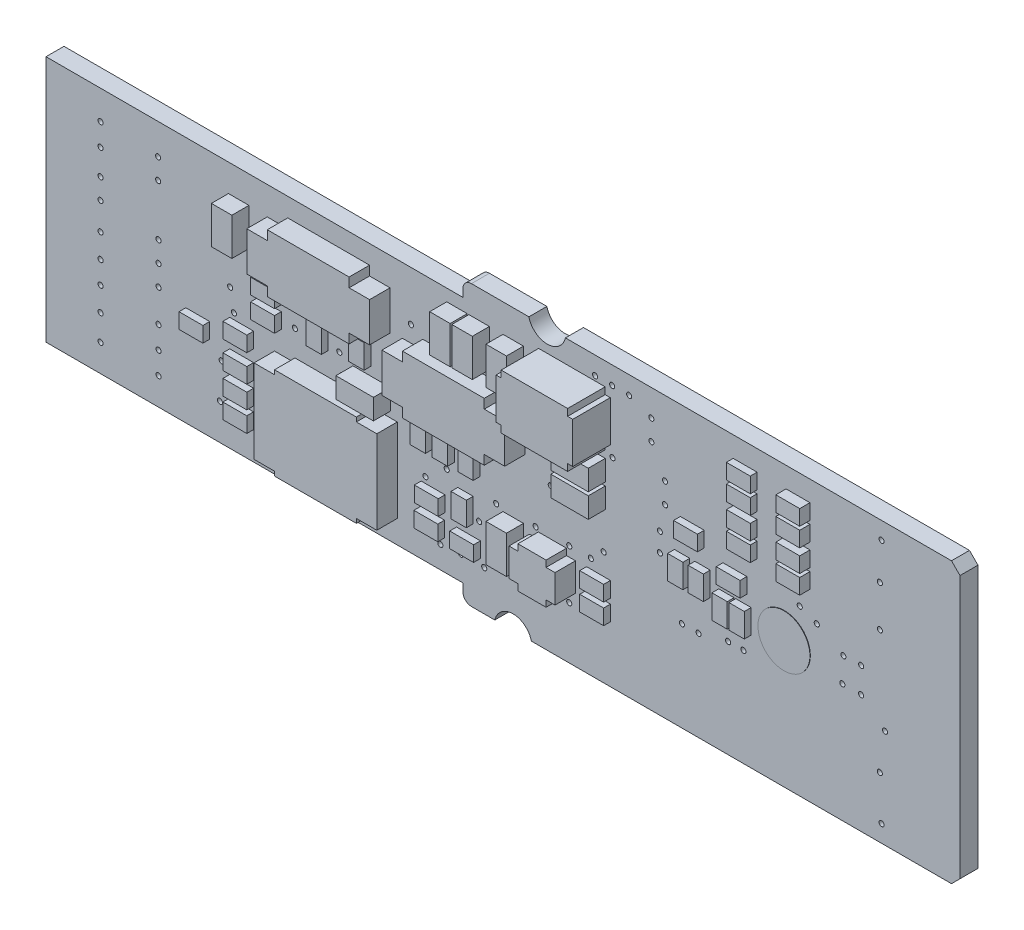
SolidWorks part; units mm, degrees
ref_plane "Front Plane" through (0, 0, 0) normal (0, 0, 1) x (1, 0, 0)
ref_plane "Top Plane" through (0, 0, 0) normal (0, 1, 0) x (1, 0, 0)
ref_plane "Right Plane" through (0, 0, 0) normal (1, 0, 0) x (0, 0, -1)
sketch "Sketch1" plane through (0, 0, 0) normal (0, 0, 1) x (1, 0, 0)
  line L0 (24.45, 14.95) -> (24.45, 14.5)
  line L1 (24.45, 14.5) -> (2.3285, 14.5)
  line L2 (2.3285, 14.5) -> (0.2516, 14.5)
  line L3 (0.2516, 14.5) -> (0, 14.5)
  line L4 (0, 14.5) -> (0, 13.75)
  line L5 (0, 13.75) -> (0, 0.75)
  line L6 (0, 0.75) -> (0, 0)
  line L7 (0, 0) -> (0.2516, 0)
  line L8 (0.2516, 0) -> (2.3285, 0)
  line L9 (2.3285, 0) -> (24.45, 0)
  line L10 (24.45, 0) -> (24.45, -0.45)
  line L11 (24.95, -0.95) -> (26.1285, -0.95)
  line L12 (26.1285, -0.95) -> (26.3188, -0.95)
  line L13 (28.4613, -0.95) -> (45.34, -0.95)
  line L14 (45.34, -0.95) -> (47.34, -0.95)
  line L15 (47.34, -0.95) -> (53.1, -0.95)
  line L16 (53.1, -0.95) -> (53.6, -0.45)
  line L17 (53.6, -0.45) -> (53.6, 14.95)
  line L18 (53.6, 14.95) -> (53.1, 15.45)
  line L19 (53.1, 15.45) -> (47.34, 15.45)
  line L20 (47.34, 15.45) -> (45.34, 15.45)
  line L21 (45.34, 15.45) -> (30.4613, 15.45)
  line L22 (28.3188, 15.45) -> (27.1285, 15.45)
  line L23 (27.1285, 15.45) -> (25.2516, 15.45)
  line L24 (25.2516, 15.45) -> (24.95, 15.45)
  arc A0 (24.95, 15.45) -> (24.45, 14.95) centre (24.95, 14.95) ccw
  arc A1 (24.45, -0.45) -> (24.95, -0.95) centre (24.95, -0.45) ccw
  arc A2 (26.3188, -0.95) -> (28.4613, -0.95) centre (27.39, -1.1999) cw
  arc A3 (30.4613, 15.45) -> (28.3188, 15.45) centre (29.3901, 15.7) cw
extrude "BOARD" add sketch "Sketch1" along normal blind 1.055 separate body
sketch "Sketch2" plane through (0, 0, 0) normal (0, 0, 1) x (1, 0, 0)
  circle A0 centre (31.95, 5) radius 0.15
  circle A1 centre (38.2697, 4.3492) radius 0.15
  circle A2 centre (37.2889, 4.3492) radius 0.15
  circle A3 centre (21, 7.3) radius 0.15
  circle A4 centre (26.4, 3.6) radius 0.15
  circle A5 centre (10.3, 4.2) radius 0.15
  circle A6 centre (11.025, 7) radius 0.15
  circle A7 centre (12.1, 10.1) radius 0.15
  circle A8 centre (22.9, 7.6) radius 0.15
  circle A9 centre (16.1, 9.8) radius 0.15
  circle A10 centre (29.6, 10.1) radius 0.15
  circle A11 centre (29, 10.8) radius 0.15
  circle A12 centre (25.4, 3.6) radius 0.15
  circle A13 centre (10.8, 8.2) radius 0.15
  circle A14 centre (47.8, 7.4841) radius 0.15
  circle A15 centre (46.76, 7.46) radius 0.15
  circle A16 centre (30.5, 7.5) radius 0.15
  circle A17 centre (29.6, 7.5) radius 0.15
  circle A18 centre (6.575, 11.5) radius 0.15
  circle A19 centre (6.575, 12.7) radius 0.15
  circle A20 centre (10.2, 2.1) radius 0.15
  circle A21 centre (6.6, 4.2) radius 0.15
  circle A22 centre (6.6, 2.9) radius 0.15
  circle A23 centre (6.6, 1.6) radius 0.15
  circle A24 centre (47.8, 6) radius 0.15
  circle A25 centre (23, 11.927) radius 0.15
  circle A26 centre (23, 11.1) radius 0.15
  circle A27 centre (46.7, 6) radius 0.15
  circle A28 centre (23.125, 1.3) radius 0.15
  circle A29 centre (14.6, 9.25) radius 0.15
  circle A30 centre (14.6, 8) radius 0.15
  circle A31 centre (28.715, 4.985) radius 0.15
  circle A32 centre (17.2, 8.1) radius 0.15
  circle A33 centre (32.7, 5.7) radius 0.15
  circle A34 centre (30.685, 2.115) radius 0.15
  circle A35 centre (35.5, 13.9) radius 0.15
  circle A36 centre (35.5, 12.7) radius 0.15
  circle A37 centre (36.3, 11.1) radius 0.15
  circle A38 centre (36.3, 9.9) radius 0.15
  circle A39 centre (36, 7.3) radius 0.15
  circle A40 centre (24.325, 1.4) radius 0.15
  circle A41 centre (22.25, 4.3) radius 0.15
  circle A42 centre (36, 8.4) radius 0.15
  circle A43 centre (23.5, 5.3) radius 0.15
  circle A44 centre (44.2, 8.7) radius 0.15
  circle A45 centre (40.9, 4.8) radius 0.15
  circle A46 centre (40, 4.8) radius 0.15
  circle A47 centre (45.2, 8.3) radius 0.15
  circle A48 centre (6.6, 8.5) radius 0.15
  circle A49 centre (6.6, 7.3) radius 0.15
  circle A50 centre (6.6, 6.1) radius 0.15
  circle A51 centre (25.8, 7.1) radius 0.15
  circle A52 centre (17.4, 7) radius 0.15
  circle A53 centre (26.4, 5) radius 0.15
  circle A54 centre (30.685, 5) radius 0.15
  circle A55 centre (25.7, 1.4) radius 0.15
  circle A56 centre (12.4, 1.2) radius 0.15
  circle A57 centre (3.2, 12.8) radius 0.15
  circle A58 centre (49, 0.05) radius 0.15
  circle A59 centre (48.9, 2.6) radius 0.15
  circle A60 centre (48.9, 9.85) radius 0.15
  circle A61 centre (49.2, 4.85) radius 0.15
  circle A62 centre (48.9, 12.25) radius 0.15
  circle A63 centre (33.22, 10.75) radius 0.15
  circle A64 centre (32.2, 14.4) radius 0.15
  circle A65 centre (33.2, 14.4) radius 0.15
  circle A66 centre (34.2, 14.4) radius 0.15
  circle A67 centre (49, 14.4443) radius 0.15
  circle A68 centre (3.2, 11.5) radius 0.15
  circle A69 centre (3.2, 10) radius 0.15
  circle A70 centre (3.2, 8.8) radius 0.15
  circle A71 centre (3.2, 7.2) radius 0.15
  circle A72 centre (3.2, 5.8) radius 0.15
  circle A73 centre (3.2, 4.5) radius 0.15
  circle A74 centre (3.2, 3.1) radius 0.15
  circle A75 centre (3.2, 1.6) radius 0.15
  circle A76 centre (21.4, 11.6) radius 0.15
extrude "PLATED HOLES" cut sketch "Sketch2" along normal through all
ref_plane "Plane1" through (0, 0, 1.055) normal (0, 0, 1) x (1, 0, 0)
sketch "Sketch3" plane through (0, 0, 1.055) normal (0, 0, 1) x (1, 0, 0)
  line L0 (40.3, 10.75) -> (40.3, 9.85)
  line L1 (40.3, 9.85) -> (41.7, 9.85)
  line L2 (41.7, 9.85) -> (41.7, 10.75)
  line L3 (41.7, 10.75) -> (40.3, 10.75)
extrude "R0201NAS-1" add sketch "Sketch3" along normal blind 0.4 separate body
sketch "Sketch4" plane through (0, 0, 1.055) normal (0, 0, 1) x (1, 0, 0)
  line L0 (25.475, 1.75) -> (25.475, 2.65)
  line L1 (25.475, 2.65) -> (24.075, 2.65)
  line L2 (24.075, 2.65) -> (24.075, 1.75)
  line L3 (24.075, 1.75) -> (25.475, 1.75)
extrude "R0201NAS-2" add sketch "Sketch4" along normal blind 0.4 separate body
sketch "Sketch5" plane through (0, 0, 1.055) normal (0, 0, 1) x (1, 0, 0)
  line L0 (23.375, 1.75) -> (23.375, 2.65)
  line L1 (23.375, 2.65) -> (21.975, 2.65)
  line L2 (21.975, 2.65) -> (21.975, 1.75)
  line L3 (21.975, 1.75) -> (23.375, 1.75)
extrude "R0201NAS-3" add sketch "Sketch5" along normal blind 0.4 separate body
sketch "Sketch6" plane through (0, 0, 1.055) normal (0, 0, 1) x (1, 0, 0)
  line L0 (8.2, 5.85) -> (8.2, 4.95)
  line L1 (8.2, 4.95) -> (9.6, 4.95)
  line L2 (9.6, 4.95) -> (9.6, 5.85)
  line L3 (9.6, 5.85) -> (8.2, 5.85)
extrude "R0201NAS-4" add sketch "Sketch6" along normal blind 0.4 separate body
sketch "Sketch7" plane through (0, 0, 1.055) normal (0, 0, 1) x (1, 0, 0)
  line L0 (10.775, 2.55) -> (10.775, 1.65)
  line L1 (10.775, 1.65) -> (12.175, 1.65)
  line L2 (12.175, 1.65) -> (12.175, 2.55)
  line L3 (12.175, 2.55) -> (10.775, 2.55)
extrude "R0201NAS-5" add sketch "Sketch7" along normal blind 0.4 separate body
sketch "Sketch8" plane through (0, 0, 1.055) normal (0, 0, 1) x (1, 0, 0)
  line L0 (10.775, 3.75) -> (10.775, 2.85)
  line L1 (10.775, 2.85) -> (12.175, 2.85)
  line L2 (12.175, 2.85) -> (12.175, 3.75)
  line L3 (12.175, 3.75) -> (10.775, 3.75)
extrude "R0201NAS-6" add sketch "Sketch8" along normal blind 0.4 separate body
sketch "Sketch9" plane through (0, 0, 1.055) normal (0, 0, 1) x (1, 0, 0)
  line L0 (24.55, 5.9) -> (25.45, 5.9)
  line L1 (25.45, 5.9) -> (25.45, 7.3)
  line L2 (25.45, 7.3) -> (24.55, 7.3)
  line L3 (24.55, 7.3) -> (24.55, 5.9)
extrude "R0201NAS-7" add sketch "Sketch9" along normal blind 0.4 separate body
sketch "Sketch10" plane through (0, 0, 1.055) normal (0, 0, 1) x (1, 0, 0)
  line L0 (21.75, 5.875) -> (22.65, 5.875)
  line L1 (22.65, 5.875) -> (22.65, 7.275)
  line L2 (22.65, 7.275) -> (21.75, 7.275)
  line L3 (21.75, 7.275) -> (21.75, 5.875)
extrude "R0201NAS-8" add sketch "Sketch10" along normal blind 0.4 separate body
sketch "Sketch11" plane through (0, 0, 1.055) normal (0, 0, 1) x (1, 0, 0)
  line L0 (12.175, 5.75) -> (12.175, 6.65)
  line L1 (12.175, 6.65) -> (10.775, 6.65)
  line L2 (10.775, 6.65) -> (10.775, 5.75)
  line L3 (10.775, 5.75) -> (12.175, 5.75)
extrude "R0201NAS-9" add sketch "Sketch11" along normal blind 0.4 separate body
sketch "Sketch12" plane through (0, 0, 1.055) normal (0, 0, 1) x (1, 0, 0)
  line L0 (12.175, 4.15) -> (12.175, 5.05)
  line L1 (12.175, 5.05) -> (10.775, 5.05)
  line L2 (10.775, 5.05) -> (10.775, 4.15)
  line L3 (10.775, 4.15) -> (12.175, 4.15)
extrude "R0201NAS-10" add sketch "Sketch12" along normal blind 0.4 separate body
sketch "Sketch13" plane through (0, 0, 1.055) normal (0, 0, 1) x (1, 0, 0)
  line L0 (13.8, 8.8) -> (13.8, 9.7)
  line L1 (13.8, 9.7) -> (12.4, 9.7)
  line L2 (12.4, 9.7) -> (12.4, 8.8)
  line L3 (12.4, 8.8) -> (13.8, 8.8)
extrude "R0201NAS-11" add sketch "Sketch13" along normal blind 0.4 separate body
sketch "Sketch14" plane through (0, 0, 1.055) normal (0, 0, 1) x (1, 0, 0)
  line L0 (19.05, 9.7) -> (18.15, 9.7)
  line L1 (18.15, 9.7) -> (18.15, 8.3)
  line L2 (18.15, 8.3) -> (19.05, 8.3)
  line L3 (19.05, 8.3) -> (19.05, 9.7)
extrude "R0201NAS-12" add sketch "Sketch14" along normal blind 0.4 separate body
sketch "Sketch15" plane through (0, 0, 1.055) normal (0, 0, 1) x (1, 0, 0)
  line L0 (22, 3.95) -> (22, 3.05)
  line L1 (22, 3.05) -> (23.4, 3.05)
  line L2 (23.4, 3.05) -> (23.4, 3.95)
  line L3 (23.4, 3.95) -> (22, 3.95)
extrude "R0201NAS-13" add sketch "Sketch15" along normal blind 0.4 separate body
sketch "Sketch16" plane through (0, 0, 1.055) normal (0, 0, 1) x (1, 0, 0)
  line L0 (25.05, 4.7) -> (24.15, 4.7)
  line L1 (24.15, 4.7) -> (24.15, 3.3)
  line L2 (24.15, 3.3) -> (25.05, 3.3)
  line L3 (25.05, 3.3) -> (25.05, 4.7)
extrude "R0201NAS-14" add sketch "Sketch16" along normal blind 0.4 separate body
sketch "Sketch17" plane through (0, 0, 1.055) normal (0, 0, 1) x (1, 0, 0)
  line L0 (23.05, 5.875) -> (23.95, 5.875)
  line L1 (23.95, 5.875) -> (23.95, 7.275)
  line L2 (23.95, 7.275) -> (23.05, 7.275)
  line L3 (23.05, 7.275) -> (23.05, 5.875)
extrude "R0201NAS-15" add sketch "Sketch17" along normal blind 0.4 separate body
sketch "Sketch18" plane through (0, 0, 1.055) normal (0, 0, 1) x (1, 0, 0)
  line L0 (13.8, 7.55) -> (13.8, 8.45)
  line L1 (13.8, 8.45) -> (12.4, 8.45)
  line L2 (12.4, 8.45) -> (12.4, 7.55)
  line L3 (12.4, 7.55) -> (13.8, 7.55)
extrude "R0201NAS-16" add sketch "Sketch18" along normal blind 0.4 separate body
sketch "Sketch19" plane through (0, 0, 1.055) normal (0, 0, 1) x (1, 0, 0)
  line L0 (15.65, 7.85) -> (16.55, 7.85)
  line L1 (16.55, 7.85) -> (16.55, 9.25)
  line L2 (16.55, 9.25) -> (15.65, 9.25)
  line L3 (15.65, 9.25) -> (15.65, 7.85)
extrude "R0201NAS-17" add sketch "Sketch19" along normal blind 0.4 separate body
sketch "Sketch20" plane through (0, 0, 1.055) normal (0, 0, 1) x (1, 0, 0)
  line L0 (31.7, 3.25) -> (31.7, 2.35)
  line L1 (31.7, 2.35) -> (33.1, 2.35)
  line L2 (33.1, 2.35) -> (33.1, 3.25)
  line L3 (33.1, 3.25) -> (31.7, 3.25)
extrude "R0201NAS-18" add sketch "Sketch20" along normal blind 0.4 separate body
sketch "Sketch21" plane through (0, 0, 1.055) normal (0, 0, 1) x (1, 0, 0)
  line L0 (31.7, 4.45) -> (31.7, 3.55)
  line L1 (31.7, 3.55) -> (33.1, 3.55)
  line L2 (33.1, 3.55) -> (33.1, 4.45)
  line L3 (33.1, 4.45) -> (31.7, 4.45)
extrude "R0201NAS-19" add sketch "Sketch21" along normal blind 0.4 separate body
sketch "Sketch22" plane through (0, 0, 0) normal (0, 0, 1) x (1, 0, 0)
  line L0 (39.25, 11.2) -> (40.15, 11.2)
  line L1 (40.15, 11.2) -> (40.15, 9.8)
  line L2 (40.15, 9.8) -> (39.25, 9.8)
  line L3 (39.25, 9.8) -> (39.25, 11.2)
extrude "R0201NAS-20" add sketch "Sketch22" against normal blind 0.4 separate body
sketch "Sketch23" plane through (0, 0, 0) normal (0, 0, 1) x (1, 0, 0)
  line L0 (39.25, 14) -> (40.15, 14)
  line L1 (40.15, 14) -> (40.15, 12.6)
  line L2 (40.15, 12.6) -> (39.25, 12.6)
  line L3 (39.25, 12.6) -> (39.25, 14)
extrude "R0201NAS-21" add sketch "Sketch23" against normal blind 0.4 separate body
sketch "Sketch24" plane through (0, 0, 1.055) normal (0, 0, 1) x (1, 0, 0)
  line L0 (41.1, 7.75) -> (41.1, 8.65)
  line L1 (41.1, 8.65) -> (39.7, 8.65)
  line L2 (39.7, 8.65) -> (39.7, 7.75)
  line L3 (39.7, 7.75) -> (41.1, 7.75)
extrude "R0201NAS-22" add sketch "Sketch24" along normal blind 0.4 separate body
sketch "Sketch25" plane through (0, 0, 1.055) normal (0, 0, 1) x (1, 0, 0)
  line L0 (38.6, 8.85) -> (38.6, 9.75)
  line L1 (38.6, 9.75) -> (37.2, 9.75)
  line L2 (37.2, 9.75) -> (37.2, 8.85)
  line L3 (37.2, 8.85) -> (38.6, 8.85)
extrude "R0201NAS-23" add sketch "Sketch25" along normal blind 0.4 separate body
sketch "Sketch26" plane through (0, 0, 0) normal (0, 0, 1) x (1, 0, 0)
  line L0 (41, 13.35) -> (41, 14.25)
  line L1 (41, 14.25) -> (42.4, 14.25)
  line L2 (42.4, 14.25) -> (42.4, 13.35)
  line L3 (42.4, 13.35) -> (41, 13.35)
extrude "R0201NAS-24" add sketch "Sketch26" against normal blind 0.4 separate body
sketch "Sketch27" plane through (0, 0, 1.055) normal (0, 0, 1) x (1, 0, 0)
  line L0 (40.45, 5.8) -> (41.35, 5.8)
  line L1 (41.35, 5.8) -> (41.35, 7.2)
  line L2 (41.35, 7.2) -> (40.45, 7.2)
  line L3 (40.45, 7.2) -> (40.45, 5.8)
extrude "R0201NAS-25" add sketch "Sketch27" along normal blind 0.4 separate body
sketch "Sketch28" plane through (0, 0, 1.055) normal (0, 0, 1) x (1, 0, 0)
  line L0 (40.3, 11.85) -> (40.3, 10.95)
  line L1 (40.3, 10.95) -> (41.7, 10.95)
  line L2 (41.7, 10.95) -> (41.7, 11.85)
  line L3 (41.7, 11.85) -> (40.3, 11.85)
extrude "R0201NAS-26" add sketch "Sketch28" along normal blind 0.4 separate body
sketch "Sketch29" plane through (0, 0, 1.055) normal (0, 0, 1) x (1, 0, 0)
  line L0 (39.45, 5.8) -> (40.35, 5.8)
  line L1 (40.35, 5.8) -> (40.35, 7.2)
  line L2 (40.35, 7.2) -> (39.45, 7.2)
  line L3 (39.45, 7.2) -> (39.45, 5.8)
extrude "R0201NAS-27" add sketch "Sketch29" along normal blind 0.4 separate body
sketch "Sketch30" plane through (0, 0, 1.055) normal (0, 0, 1) x (1, 0, 0)
  line L0 (40.3, 13.15) -> (40.3, 12.25)
  line L1 (40.3, 12.25) -> (41.7, 12.25)
  line L2 (41.7, 12.25) -> (41.7, 13.15)
  line L3 (41.7, 13.15) -> (40.3, 13.15)
extrude "R0201NAS-28" add sketch "Sketch30" along normal blind 0.4 separate body
sketch "Sketch31" plane through (0, 0, 1.055) normal (0, 0, 1) x (1, 0, 0)
  line L0 (38.05, 6.5) -> (38.95, 6.5)
  line L1 (38.95, 6.5) -> (38.95, 7.9)
  line L2 (38.95, 7.9) -> (38.05, 7.9)
  line L3 (38.05, 7.9) -> (38.05, 6.5)
extrude "R0201NAS-29" add sketch "Sketch31" along normal blind 0.4 separate body
sketch "Sketch32" plane through (0, 0, 1.055) normal (0, 0, 1) x (1, 0, 0)
  line L0 (40.3, 14.25) -> (40.3, 13.35)
  line L1 (40.3, 13.35) -> (41.7, 13.35)
  line L2 (41.7, 13.35) -> (41.7, 14.25)
  line L3 (41.7, 14.25) -> (40.3, 14.25)
extrude "R0201NAS-30" add sketch "Sketch32" along normal blind 0.4 separate body
sketch "Sketch33" plane through (0, 0, 0) normal (0, 0, 1) x (1, 0, 0)
  line L0 (37.3, 9.55) -> (37.3, 10.45)
  line L1 (37.3, 10.45) -> (38.7, 10.45)
  line L2 (38.7, 10.45) -> (38.7, 9.55)
  line L3 (38.7, 9.55) -> (37.3, 9.55)
extrude "R0201NAS-31" add sketch "Sketch33" against normal blind 0.4 separate body
sketch "Sketch34" plane through (0, 0, 0) normal (0, 0, 1) x (1, 0, 0)
  line L0 (41, 9.45) -> (41, 10.35)
  line L1 (41, 10.35) -> (42.4, 10.35)
  line L2 (42.4, 10.35) -> (42.4, 9.45)
  line L3 (42.4, 9.45) -> (41, 9.45)
extrude "R0201NAS-32" add sketch "Sketch34" against normal blind 0.4 separate body
sketch "Sketch35" plane through (0, 0, 0) normal (0, 0, 1) x (1, 0, 0)
  line L0 (37.3, 10.55) -> (37.3, 11.45)
  line L1 (37.3, 11.45) -> (38.7, 11.45)
  line L2 (38.7, 11.45) -> (38.7, 10.55)
  line L3 (38.7, 10.55) -> (37.3, 10.55)
extrude "R0201NAS-33" add sketch "Sketch35" against normal blind 0.4 separate body
sketch "Sketch36" plane through (0, 0, 0) normal (0, 0, 1) x (1, 0, 0)
  line L0 (41, 10.55) -> (41, 11.45)
  line L1 (41, 11.45) -> (42.4, 11.45)
  line L2 (42.4, 11.45) -> (42.4, 10.55)
  line L3 (42.4, 10.55) -> (41, 10.55)
extrude "R0201NAS-34" add sketch "Sketch36" against normal blind 0.4 separate body
sketch "Sketch37" plane through (0, 0, 0) normal (0, 0, 1) x (1, 0, 0)
  line L0 (37.3, 12.25) -> (37.3, 13.15)
  line L1 (37.3, 13.15) -> (38.7, 13.15)
  line L2 (38.7, 13.15) -> (38.7, 12.25)
  line L3 (38.7, 12.25) -> (37.3, 12.25)
extrude "R0201NAS-35" add sketch "Sketch37" against normal blind 0.4 separate body
sketch "Sketch38" plane through (0, 0, 0) normal (0, 0, 1) x (1, 0, 0)
  line L0 (41, 12.25) -> (41, 13.15)
  line L1 (41, 13.15) -> (42.4, 13.15)
  line L2 (42.4, 13.15) -> (42.4, 12.25)
  line L3 (42.4, 12.25) -> (41, 12.25)
extrude "R0201NAS-36" add sketch "Sketch38" against normal blind 0.4 separate body
sketch "Sketch39" plane through (0, 0, 0) normal (0, 0, 1) x (1, 0, 0)
  line L0 (37.3, 13.35) -> (37.3, 14.25)
  line L1 (37.3, 14.25) -> (38.7, 14.25)
  line L2 (38.7, 14.25) -> (38.7, 13.35)
  line L3 (38.7, 13.35) -> (37.3, 13.35)
extrude "R0201NAS-37" add sketch "Sketch39" against normal blind 0.4 separate body
sketch "Sketch40" plane through (0, 0, 1.055) normal (0, 0, 1) x (1, 0, 0)
  line L0 (36.85, 6.5) -> (37.75, 6.5)
  line L1 (37.75, 6.5) -> (37.75, 7.9)
  line L2 (37.75, 7.9) -> (36.85, 7.9)
  line L3 (36.85, 7.9) -> (36.85, 6.5)
extrude "R0201NAS-38" add sketch "Sketch40" along normal blind 0.4 separate body
sketch "J0M09NAS_CE-1 [0]" plane through (0, 0, 1.055) normal (0, 0, 1) x (1, 0, 0)
  line L0 (50.35, -0.5) -> (50.35, 15)
  line L1 (50.35, 15) -> (53.3, 15)
  line L2 (53.3, 15) -> (53.3, -0.5)
  line L3 (53.3, -0.5) -> (50.35, -0.5)
sketch "Sketch42" plane through (0, 0, 0) normal (0, 0, 1) x (1, 0, 0)
  circle A0 centre (35, 3.8) radius 1.524
extrude "FIDGLOBAL-1" add sketch "Sketch42" against normal blind 0.0254 separate body
sketch "Sketch43" plane through (0, 0, 1.055) normal (0, 0, 1) x (1, 0, 0)
  circle A0 centre (43.3, 6.5) radius 1.524
extrude "FIDGLOBAL-2" add sketch "Sketch43" along normal blind 0.0254 separate body
sketch "Sketch44" plane through (0, 0, 0) normal (0, 0, 1) x (1, 0, 0)
  line L0 (0.475, 9.3) -> (0.475, 5.2)
  line L1 (0.475, 5.2) -> (9.325, 5.2)
  line L2 (9.325, 5.2) -> (9.325, 9.3)
  line L3 (9.325, 9.3) -> (0.475, 9.3)
extrude "R0203NAS_CE-1" add sketch "Sketch44" against normal blind 0.7 separate body
sketch "Sketch45" plane through (0, 0, 0) normal (0, 0, 1) x (1, 0, 0)
  line L0 (0.45, 13.5) -> (0.45, 9.4)
  line L1 (0.45, 9.4) -> (9.3, 9.4)
  line L2 (9.3, 9.4) -> (9.3, 13.5)
  line L3 (9.3, 13.5) -> (0.45, 13.5)
extrude "R0203NAS_CE-2" add sketch "Sketch45" against normal blind 0.7 separate body
sketch "Sketch46" plane through (0, 0, 0) normal (0, 0, 1) x (1, 0, 0)
  line L0 (0.45, 5.1) -> (0.45, 1)
  line L1 (0.45, 1) -> (9.3, 1)
  line L2 (9.3, 1) -> (9.3, 5.1)
  line L3 (9.3, 5.1) -> (0.45, 5.1)
extrude "R0203NAS_CE-3" add sketch "Sketch46" against normal blind 0.7 separate body
sketch "Sketch47" plane through (0, 0, 1.055) normal (0, 0, 1) x (1, 0, 0)
  line L0 (28.59, 13.73) -> (28.59, 11.33)
  line L1 (28.59, 11.33) -> (28.89, 11.33)
  line L2 (28.89, 11.33) -> (28.89, 10.93)
  line L3 (28.89, 10.93) -> (32.79, 10.93)
  line L4 (32.79, 10.93) -> (32.79, 11.33)
  line L5 (32.79, 11.33) -> (33.09, 11.33)
  line L6 (33.09, 11.33) -> (33.09, 13.73)
  line L7 (33.09, 13.73) -> (32.79, 13.73)
  line L8 (32.79, 13.73) -> (32.79, 14.13)
  line L9 (32.79, 14.13) -> (28.89, 14.13)
  line L10 (28.89, 14.13) -> (28.89, 13.73)
  line L11 (28.89, 13.73) -> (28.59, 13.73)
extrude "CE211NAS-1" add sketch "Sketch47" along normal blind 2.2 separate body
sketch "Sketch48" plane through (0, 0, 1.055) normal (0, 0, 1) x (1, 0, 0)
  line L0 (28, 13.8) -> (26.8, 13.8)
  line L1 (26.8, 13.8) -> (26.8, 11.6)
  line L2 (26.8, 11.6) -> (28, 11.6)
  line L3 (28, 11.6) -> (28, 13.8)
extrude "C0204NAS-1" add sketch "Sketch48" along normal blind 1 separate body
sketch "Sketch49" plane through (0, 0, 1.055) normal (0, 0, 1) x (1, 0, 0)
  line L0 (28, 4.8) -> (26.8, 4.8)
  line L1 (26.8, 4.8) -> (26.8, 2.6)
  line L2 (26.8, 2.6) -> (28, 2.6)
  line L3 (28, 2.6) -> (28, 4.8)
extrude "C0204NAS-2" add sketch "Sketch49" along normal blind 1 separate body
sketch "Sketch50" plane through (0, 0, 1.055) normal (0, 0, 1) x (1, 0, 0)
  line L0 (32.8, 7.9) -> (32.8, 9.1)
  line L1 (32.8, 9.1) -> (30.6, 9.1)
  line L2 (30.6, 9.1) -> (30.6, 7.9)
  line L3 (30.6, 7.9) -> (32.8, 7.9)
extrude "C0204NAS-3" add sketch "Sketch50" along normal blind 1 separate body
sketch "Sketch51" plane through (0, 0, 1.055) normal (0, 0, 1) x (1, 0, 0)
  line L0 (24.7, 13.8) -> (23.5, 13.8)
  line L1 (23.5, 13.8) -> (23.5, 11.6)
  line L2 (23.5, 11.6) -> (24.7, 11.6)
  line L3 (24.7, 11.6) -> (24.7, 13.8)
extrude "C0204NAS-4" add sketch "Sketch51" along normal blind 1 separate body
sketch "Sketch52" plane through (0, 0, 1.055) normal (0, 0, 1) x (1, 0, 0)
  line L0 (18, 7.8) -> (18, 6.6)
  line L1 (18, 6.6) -> (20.2, 6.6)
  line L2 (20.2, 6.6) -> (20.2, 7.8)
  line L3 (20.2, 7.8) -> (18, 7.8)
extrude "C0204NAS-5" add sketch "Sketch52" along normal blind 1 separate body
sketch "Sketch53" plane through (0, 0, 1.055) normal (0, 0, 1) x (1, 0, 0)
  line L0 (11.9, 12.9) -> (10.7, 12.9)
  line L1 (10.7, 12.9) -> (10.7, 10.7)
  line L2 (10.7, 10.7) -> (11.9, 10.7)
  line L3 (11.9, 10.7) -> (11.9, 12.9)
extrude "C0204NAS-6" add sketch "Sketch53" along normal blind 1 separate body
sketch "Sketch54" plane through (0, 0, 1.055) normal (0, 0, 1) x (1, 0, 0)
  line L0 (26, 13.8) -> (24.8, 13.8)
  line L1 (24.8, 13.8) -> (24.8, 11.6)
  line L2 (24.8, 11.6) -> (26, 11.6)
  line L3 (26, 11.6) -> (26, 13.8)
extrude "C0204NAS-7" add sketch "Sketch54" along normal blind 1 separate body
sketch "Sketch55" plane through (0, 0, 1.055) normal (0, 0, 1) x (1, 0, 0)
  line L0 (32.8, 9.3) -> (32.8, 10.5)
  line L1 (32.8, 10.5) -> (30.6, 10.5)
  line L2 (30.6, 10.5) -> (30.6, 9.3)
  line L3 (30.6, 9.3) -> (32.8, 9.3)
extrude "C0204NAS-8" add sketch "Sketch55" along normal blind 1 separate body
sketch "Sketch56" plane through (0, 0, 1.055) normal (0, 0, 1) x (1, 0, 0)
  line L0 (43.4, 14.25) -> (43.4, 13.35)
  line L1 (43.4, 13.35) -> (44.8, 13.35)
  line L2 (44.8, 13.35) -> (44.8, 14.25)
  line L3 (44.8, 14.25) -> (43.4, 14.25)
extrude "C0215NAS-1" add sketch "Sketch56" along normal blind 0.6 separate body
sketch "Sketch57" plane through (0, 0, 1.055) normal (0, 0, 1) x (1, 0, 0)
  line L0 (43.4, 13.15) -> (43.4, 12.25)
  line L1 (43.4, 12.25) -> (44.8, 12.25)
  line L2 (44.8, 12.25) -> (44.8, 13.15)
  line L3 (44.8, 13.15) -> (43.4, 13.15)
extrude "C0215NAS-2" add sketch "Sketch57" along normal blind 0.6 separate body
sketch "Sketch58" plane through (0, 0, 1.055) normal (0, 0, 1) x (1, 0, 0)
  line L0 (43.4, 11.85) -> (43.4, 10.95)
  line L1 (43.4, 10.95) -> (44.8, 10.95)
  line L2 (44.8, 10.95) -> (44.8, 11.85)
  line L3 (44.8, 11.85) -> (43.4, 11.85)
extrude "C0215NAS-3" add sketch "Sketch58" along normal blind 0.6 separate body
sketch "Sketch59" plane through (0, 0, 1.055) normal (0, 0, 1) x (1, 0, 0)
  line L0 (43.4, 10.75) -> (43.4, 9.85)
  line L1 (43.4, 9.85) -> (44.8, 9.85)
  line L2 (44.8, 9.85) -> (44.8, 10.75)
  line L3 (44.8, 10.75) -> (43.4, 10.75)
extrude "C0215NAS-4" add sketch "Sketch59" along normal blind 0.6 separate body
sketch "Sketch60" plane through (0, 0, 0) normal (0, 0, 1) x (1, 0, 0)
  line L0 (43.4, 9.45) -> (43.4, 10.35)
  line L1 (43.4, 10.35) -> (44.8, 10.35)
  line L2 (44.8, 10.35) -> (44.8, 9.45)
  line L3 (44.8, 9.45) -> (43.4, 9.45)
extrude "C0215NAS-5" add sketch "Sketch60" against normal blind 0.6 separate body
sketch "Sketch61" plane through (0, 0, 0) normal (0, 0, 1) x (1, 0, 0)
  line L0 (43.4, 10.55) -> (43.4, 11.45)
  line L1 (43.4, 11.45) -> (44.8, 11.45)
  line L2 (44.8, 11.45) -> (44.8, 10.55)
  line L3 (44.8, 10.55) -> (43.4, 10.55)
extrude "C0215NAS-6" add sketch "Sketch61" against normal blind 0.6 separate body
sketch "Sketch62" plane through (0, 0, 0) normal (0, 0, 1) x (1, 0, 0)
  line L0 (43.4, 12.25) -> (43.4, 13.15)
  line L1 (43.4, 13.15) -> (44.8, 13.15)
  line L2 (44.8, 13.15) -> (44.8, 12.25)
  line L3 (44.8, 12.25) -> (43.4, 12.25)
extrude "C0215NAS-7" add sketch "Sketch62" against normal blind 0.6 separate body
sketch "Sketch63" plane through (0, 0, 0) normal (0, 0, 1) x (1, 0, 0)
  line L0 (43.4, 13.35) -> (43.4, 14.25)
  line L1 (43.4, 14.25) -> (44.8, 14.25)
  line L2 (44.8, 14.25) -> (44.8, 13.35)
  line L3 (44.8, 13.35) -> (43.4, 13.35)
extrude "C0215NAS-8" add sketch "Sketch63" against normal blind 0.6 separate body
sketch "Sketch64" plane through (0, 0, 1.055) normal (0, 0, 1) x (1, 0, 0)
  line L0 (28.35, 2.775) -> (28.875, 2.775)
  line L1 (28.875, 2.775) -> (28.875, 2.4)
  line L2 (28.875, 2.4) -> (30.525, 2.4)
  line L3 (30.525, 2.4) -> (30.525, 2.775)
  line L4 (30.525, 2.775) -> (31.05, 2.775)
  line L5 (31.05, 2.775) -> (31.05, 4.425)
  line L6 (31.05, 4.425) -> (30.525, 4.425)
  line L7 (30.525, 4.425) -> (30.525, 4.8)
  line L8 (30.525, 4.8) -> (28.875, 4.8)
  line L9 (28.875, 4.8) -> (28.875, 4.425)
  line L10 (28.875, 4.425) -> (28.35, 4.425)
  line L11 (28.35, 4.425) -> (28.35, 2.775)
extrude "Z0562NAS-1" add sketch "Sketch64" along normal blind 1.2 separate body
sketch "Sketch65" plane through (0, 0, 1.055) normal (0, 0, 1) x (1, 0, 0)
  line L0 (20.9, 10.65) -> (22.1, 10.65)
  line L1 (22.1, 10.65) -> (22.1, 11.2)
  line L2 (22.1, 11.2) -> (26.9, 11.2)
  line L3 (26.9, 11.2) -> (26.9, 10.65)
  line L4 (26.9, 10.65) -> (28.1, 10.65)
  line L5 (28.1, 10.65) -> (28.1, 8.35)
  line L6 (28.1, 8.35) -> (26.9, 8.35)
  line L7 (26.9, 8.35) -> (26.9, 7.8)
  line L8 (26.9, 7.8) -> (22.1, 7.8)
  line L9 (22.1, 7.8) -> (22.1, 8.35)
  line L10 (22.1, 8.35) -> (20.9, 8.35)
  line L11 (20.9, 8.35) -> (20.9, 10.65)
extrude "Z0898NAS-1" add sketch "Sketch65" along normal blind 1.2 separate body
sketch "Sketch66" plane through (0, 0, 1.055) normal (0, 0, 1) x (1, 0, 0)
  line L0 (20.175, 10.55) -> (18.975, 10.55)
  line L1 (18.975, 10.55) -> (18.975, 10)
  line L2 (18.975, 10) -> (14.175, 10)
  line L3 (14.175, 10) -> (14.175, 10.55)
  line L4 (14.175, 10.55) -> (12.975, 10.55)
  line L5 (12.975, 10.55) -> (12.975, 12.85)
  line L6 (12.975, 12.85) -> (14.175, 12.85)
  line L7 (14.175, 12.85) -> (14.175, 13.4)
  line L8 (14.175, 13.4) -> (18.975, 13.4)
  line L9 (18.975, 13.4) -> (18.975, 12.85)
  line L10 (18.975, 12.85) -> (20.175, 12.85)
  line L11 (20.175, 12.85) -> (20.175, 10.55)
extrude "Z0898NAS-2" add sketch "Sketch66" along normal blind 1.2 separate body
sketch "Sketch67" plane through (0, 0, 1.055) normal (0, 0, 1) x (1, 0, 0)
  line L0 (19.4, 6.5) -> (14.6, 6.5)
  line L1 (14.6, 6.5) -> (14.6, 6.25)
  line L2 (14.6, 6.25) -> (13.4, 6.25)
  line L3 (13.4, 6.25) -> (13.4, 1.35)
  line L4 (13.4, 1.35) -> (14.6, 1.35)
  line L5 (14.6, 1.35) -> (14.6, 1.1)
  line L6 (14.6, 1.1) -> (19.4, 1.1)
  line L7 (19.4, 1.1) -> (19.4, 1.35)
  line L8 (19.4, 1.35) -> (20.6, 1.35)
  line L9 (20.6, 1.35) -> (20.6, 6.25)
  line L10 (20.6, 6.25) -> (19.4, 6.25)
  line L11 (19.4, 6.25) -> (19.4, 6.5)
extrude "Z0G58NAS-1" add sketch "Sketch67" along normal blind 1.2 separate body
